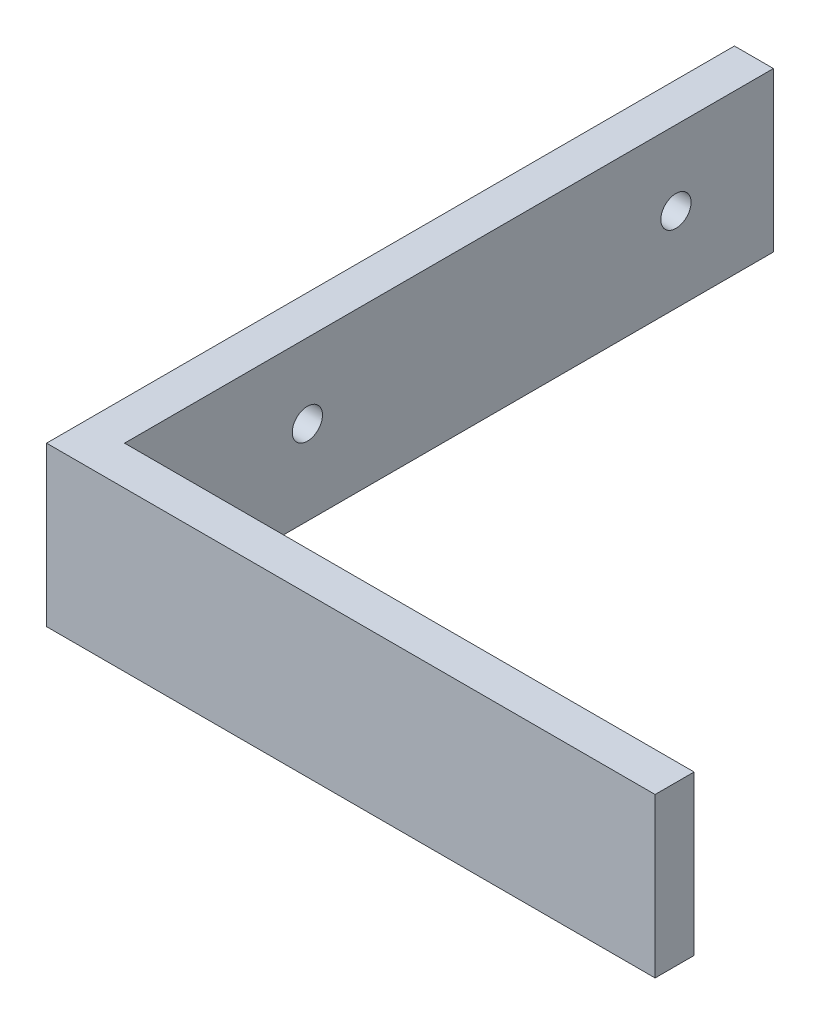
SolidWorks part; units mm, degrees
ref_plane "前视基准面" through (0, 0, 0) normal (0, 0, 1) x (1, 0, 0)
ref_plane "上视基准面" through (0, 0, 0) normal (0, 1, 0) x (1, 0, 0)
ref_plane "右视基准面" through (0, 0, 0) normal (1, 0, 0) x (0, 0, -1)
sketch "草图1" plane through (0, 0, 0) normal (0, 0, 1) x (1, 0, 0)
  line L2 (-29.15, 4.6184) -> (-29.15, -3.6184) construction
  line L3 (-29.15, 8.15) -> (-29.15, -8.15)
  line L4 (27.2634, -8) -> (27.2634, 8)
  line L5 (27.2634, 8) -> (-27.2634, 8)
  line L6 (-27.2634, 8) -> (-27.2634, -8)
  line L7 (-27.2634, -8) -> (27.2634, -8)
  line L8 (27.2634, -8.15) -> (27.2634, 8.15)
  line L21 (-27.2634, 8.15) -> (27.2634, 8.15)
  line L22 (-29.15, 8.15) -> (27.2634, 8.15)
  line L23 (-29.15, 8.15) -> (-35.15, 8.15)
  line L24 (27.2634, -8.15) -> (-27.2634, -8.15)
  line L25 (27.2634, -8.15) -> (-29.15, -8.15)
  line L26 (-29.15, 8.15) -> (-29.15, -8.15)
  line L27 (-29.15, -8.15) -> (-35.15, -8.15)
  line L28 (-35.15, 8.15) -> (-35.15, -8.15)
  dimension "D2" = 6
  dimension "D1" = 0
  dimension "D4" = 0.15
  dimension "D5" = 0.15
extrude "凸台-拉伸1" add sketch "草图1" along normal blind 4
sketch "草图3" plane through (-35.15, 0, 0) normal (-1, 0, 0) x (0, 0, 1)
  line L1 (4, 8.15) -> (-66.55, 8.15)
  line L2 (4, 8.15) -> (4, -8.15)
  line L3 (4, -8.15) -> (-66.55, -8.15)
  line L4 (-66.55, 8.15) -> (-66.55, -8.15)
  circle A0 centre (-56.55, 0.5) radius 1.5 construction
  circle A1 centre (-56.55, 0.5) radius 1.55
  circle A2 centre (-18.75, 0.5) radius 1.55
  dimension "D2" = 3.1
  dimension "D1" = 10
extrude "凸台-拉伸3" add sketch "草图3" against normal blind 4
